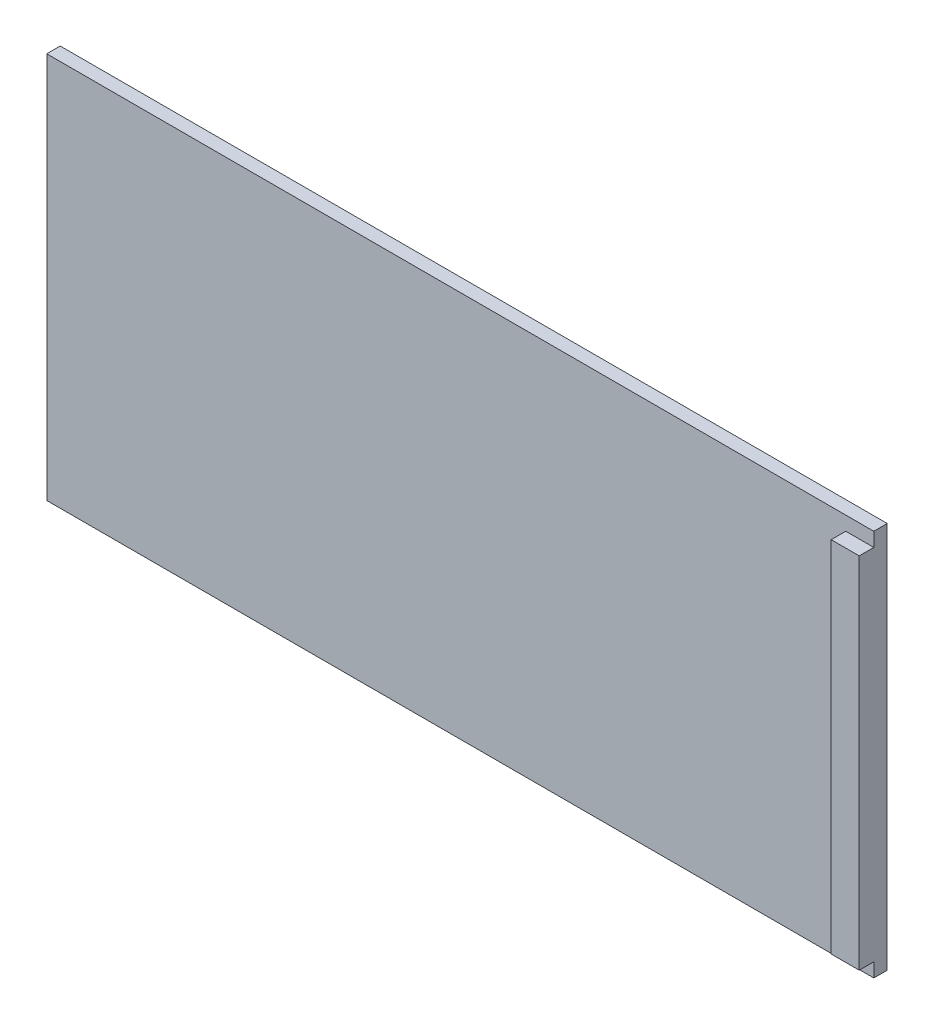
SolidWorks part; units mm, degrees
ref_plane "Front Plane" through (0, 0, 0) normal (0, 0, 1) x (1, 0, 0)
ref_plane "Top Plane" through (0, 0, 0) normal (0, 1, 0) x (1, 0, 0)
ref_plane "Right Plane" through (0, 0, 0) normal (1, 0, 0) x (0, 0, -1)
sketch "Sketch1" plane through (0, 0, 0) normal (0, 0, 1) x (1, 0, 0)
  line L1 (0, 0) -> (74.93, 0)
  line L2 (0, 0) -> (0, 35.052)
  line L3 (0, 35.052) -> (74.93, 35.052)
  line L4 (74.93, 0) -> (74.93, 35.052)
  dimension "D1" = 74.93
  dimension "D2" = 35.052
extrude "Boss-Extrude1" add sketch "Sketch1" along normal blind 1.2192
sketch "Sketch2" plane through (0, 0, 1.2192) normal (0, 0, 1) x (1, 0, 0)
  line L0 (74.93, 0) -> (74.93, 35.052) construction
  line L1 (74.93, 33.782) -> (72.39, 33.782)
  line L2 (74.93, 33.782) -> (74.93, 1.27)
  line L3 (74.93, 1.27) -> (72.39, 1.27)
  line L4 (72.39, 33.782) -> (72.39, 1.27)
  line L5 (74.93, 35.052) -> (0, 35.052) construction
  line L6 (0, 0) -> (74.93, 0) construction
  dimension "D1" = 1.27
  dimension "D2" = 1.27
  dimension "D3" = 2.54
  dimension "D4" = 32.512
extrude "Boss-Extrude2" add sketch "Sketch2" along normal blind 1.3208
